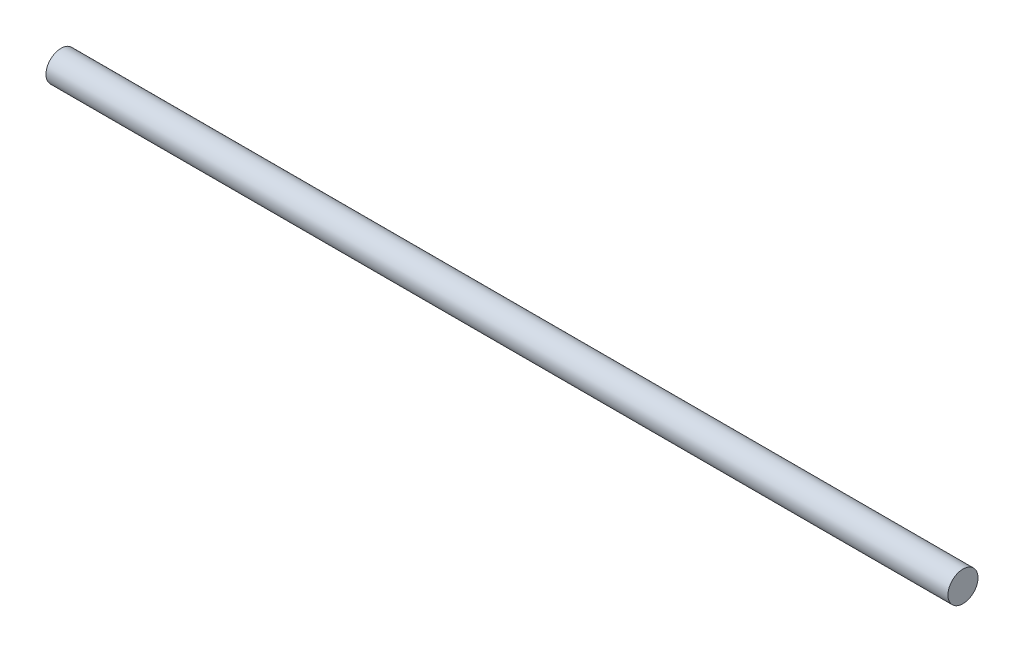
SolidWorks part; units mm, degrees
ref_plane "Alzado" through (0, 0, 0) normal (0, 0, 1) x (1, 0, 0)
ref_plane "Planta" through (0, 0, 0) normal (0, 1, 0) x (1, 0, 0)
ref_plane "Vista lateral" through (0, 0, 0) normal (1, 0, 0) x (0, 0, -1)
sketch "Croquis1" plane through (0, 0, 0) normal (1, 0, 0) x (0, 0, -1)
  circle A0 centre (0, 0) radius 1
  dimension "D1" = 2
extrude "Saliente-Extruir1" add sketch "Croquis1" along normal blind 60
